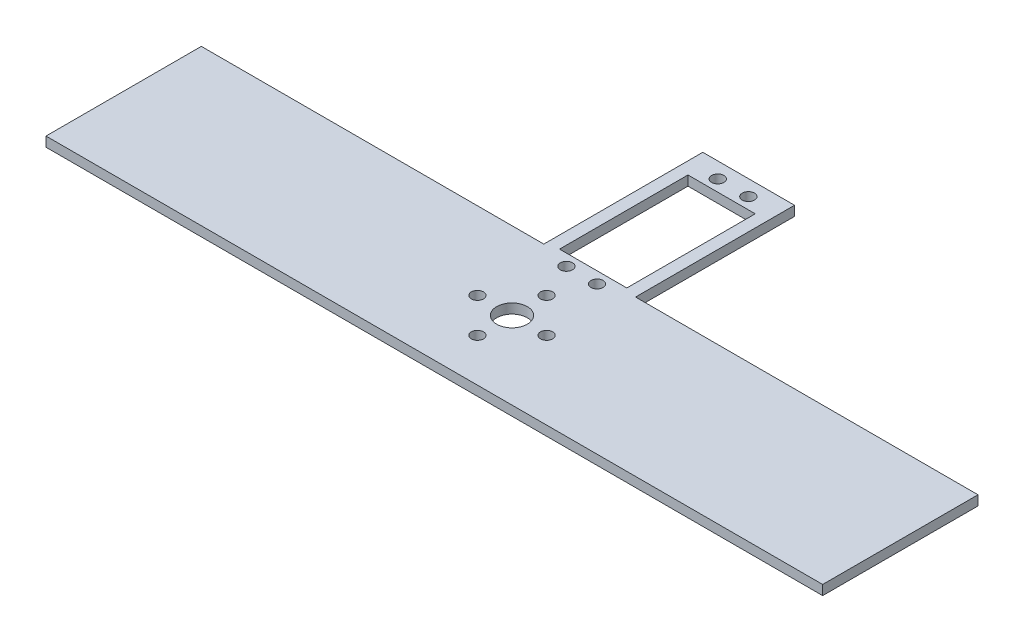
SolidWorks part; units mm, degrees
ref_plane "Front" through (0, 0, 0) normal (0, 0, 1) x (1, 0, 0)
ref_plane "Top" through (0, 0, 0) normal (0, 1, 0) x (1, 0, 0)
ref_plane "Right" through (0, 0, 0) normal (1, 0, 0) x (0, 0, -1)
sketch "Sketch1" plane through (0, 0, 0) normal (0, 1, 0) x (1, 0, 0)
  line L0 (0, -25.4) -> (254, -25.4)
  line L1 (0, 0) -> (254, 0)
  line L2 (0, 0) -> (0, -50.8)
  line L3 (0, -50.8) -> (254, -50.8)
  line L4 (254, 0) -> (254, -50.8)
  line L7 (115.2643, 0) -> (138.7357, 0)
  line L9 (127, -25.4) -> (127, 32.2)
  line L10 (127, 32.2) -> (127, 46.8974)
  line L11 (122, 46.8974) -> (132, 46.8974)
  line L12 (122, -2.6026) -> (132, -2.6026)
  line L13 (112, 0) -> (112, 52)
  line L14 (112, 52) -> (142, 52)
  line L15 (142, 52) -> (142, 0)
  line L16 (127, -2.6026) -> (127, 46.8974)
  line L17 (116, 22.1474) -> (138, 22.1474)
  line L18 (116, 1.1474) -> (116, 43.1474)
  line L19 (116, 1.1474) -> (138, 1.1474)
  line L20 (138, 1.1474) -> (138, 43.1474)
  line L21 (138, 43.1474) -> (116, 43.1474)
  circle A0 centre (127, -25.4) radius 11.3137
  circle A1 centre (127, -36.7137) radius 2
  circle A2 centre (138.3137, -25.4) radius 2
  circle A3 centre (127, -14.0863) radius 2
  circle A4 centre (115.6863, -25.4) radius 2
  circle A5 centre (127, -25.4) radius 5
  circle A6 centre (122, -2.6026) radius 2
  circle A7 centre (132, -2.6026) radius 2
  circle A8 centre (122, 46.8974) radius 2
  circle A9 centre (132, 46.8974) radius 2
  point P25 (127, 46.8974)
  point P28 (127, -2.6026)
  point P40 (127, 22.1474)
  point P43 (116, 22.1474)
  dimension "D3" = 57.6
  dimension "D8" = 30
  dimension "D1" = 254
  dimension "D2" = 50.8
  dimension "D4" = 10
  dimension "D5" = 10
  dimension "D6" = 49.5
  dimension "D7" = 14.6974
  dimension "D9" = 15
  dimension "D10" = 22
  dimension "D11" = 42
  dimension "D12" = 52
extrude "Boss-Extrude1" add sketch "Sketch1" along normal blind 3.175
